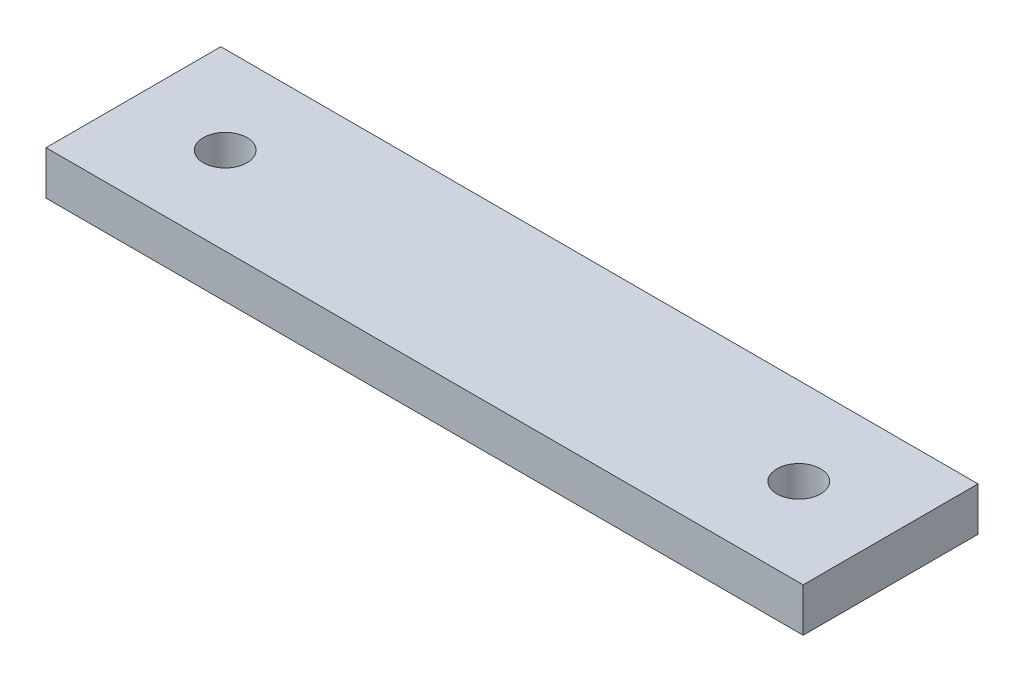
SolidWorks part; units mm, degrees
ref_plane "Front Plane" through (0, 0, 0) normal (0, 0, 1) x (1, 0, 0)
ref_plane "Top Plane" through (0, 0, 0) normal (0, 1, 0) x (1, 0, 0)
ref_plane "Right Plane" through (0, 0, 0) normal (1, 0, 0) x (0, 0, -1)
sketch "Sketch1" plane through (0, 0, 0) normal (0, 1, 0) x (1, 0, 0)
  line L1 (-165, -38.1) -> (165, -38.1)
  line L2 (-165, -38.1) -> (-165, 38.1)
  line L3 (-165, 38.1) -> (165, 38.1)
  line L4 (165, -38.1) -> (165, 38.1)
  line L5 (-165, -38.1) -> (165, 38.1) construction
  line L6 (-165, 38.1) -> (165, -38.1) construction
  circle A0 centre (-125, 0) radius 9.525
  circle A1 centre (125, 0) radius 9.525
  point P0 (0, 0)
  point P5 (0, 0)
  point P6 (0, 0)
  dimension "D3" = 19.05
  dimension "D1" = 76.2
  dimension "D2" = 330
extrude "Boss-Extrude1" add sketch "Sketch1" along normal blind 19.05
